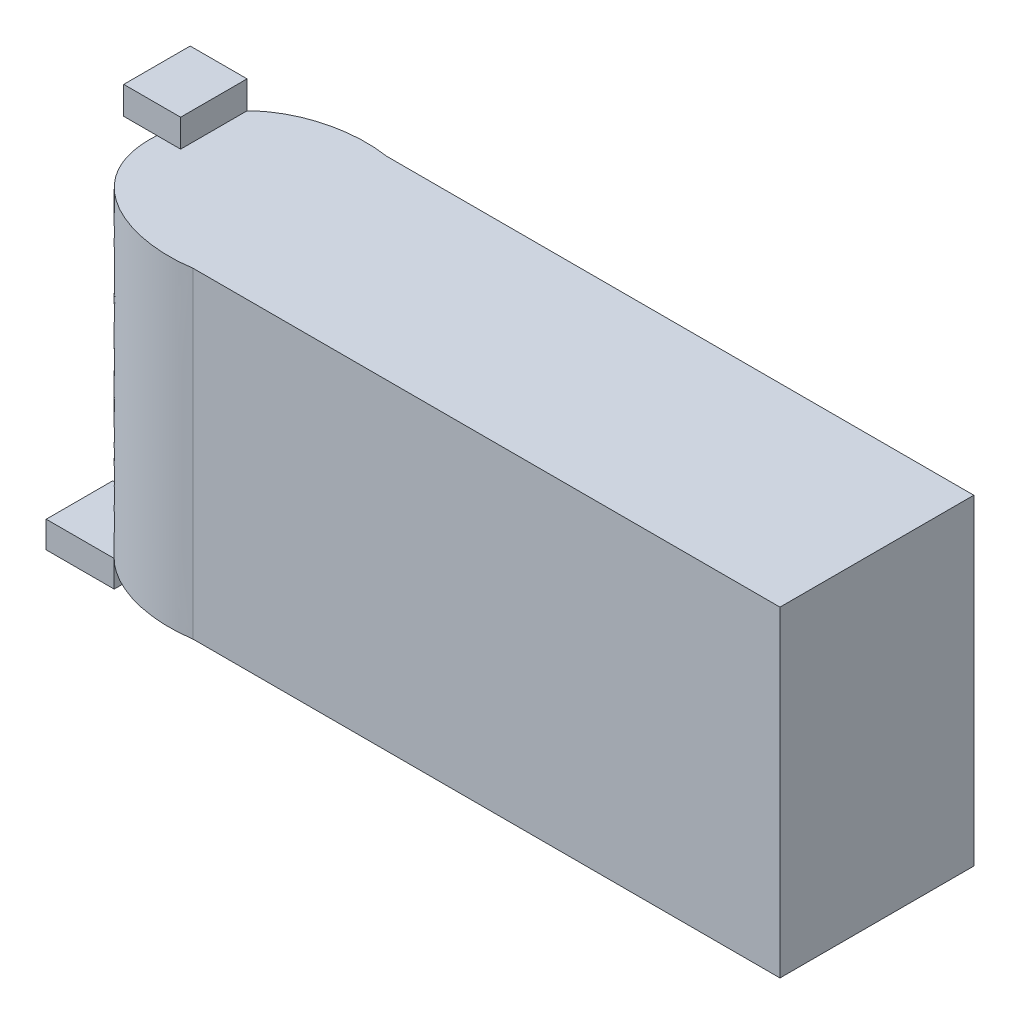
SolidWorks part; units mm, degrees
ref_plane "Front Plane" through (0, 0, 0) normal (0, 0, 1) x (1, 0, 0)
ref_plane "Top Plane" through (0, 0, 0) normal (0, 1, 0) x (1, 0, 0)
ref_plane "Right Plane" through (0, 0, 0) normal (1, 0, 0) x (0, 0, -1)
sketch "Sketch2" plane through (0, 0, 0) normal (0, 1, 0) x (1, 0, 0)
  line L0 (-26.5, 0) -> (-38.5, 0) construction
  line L1 (-26.5, -8.75) -> (26.5, -8.75)
  line L2 (-26.5, -8.75) -> (-26.5, 8.75)
  line L3 (-26.5, 8.75) -> (26.5, 8.75)
  line L4 (26.5, -8.75) -> (26.5, 8.75)
  line L5 (-26.5, -8.75) -> (26.5, 8.75) construction
  line L6 (-26.5, 8.75) -> (26.5, -8.75) construction
  line L7 (-26.5, 6.75) -> (-35.5, 6.75) construction
  line L8 (-26.5, 8.75) -> (-30.5, 8.75) construction
  spline S0 degree 3 poles (-26.5, 8.75) (-31.8446, 9.5987) (-38.9648, 6.9537) (-38.5, 0) knots 0 0 0 0 1 1 1 1
  spline S1 degree 3 poles (-26.5, -8.75) (-31.8446, -9.5987) (-38.9648, -6.9537) (-38.5, 0) knots 0 0 0 0 1 1 1 1
  point P0 (0, 0)
  dimension "D1" = 53
  dimension "D2" = 17.5
  dimension "D3" = 12
  dimension "D4" = 9
  dimension "D5" = 2
  dimension "D6" = 4
extrude "Boss-Extrude1" add sketch "Sketch2" along normal blind 29 contours L1 L4 L3 L2 | S1 L2 S0
sketch "Sketch3" plane through (0, 29, 0) normal (0, 1, 0) x (1, 0, 0)
  line L0 (-38.5, 6) -> (-36.3652, 6)
  line L1 (-38.5, 0) -> (-41.5, 0)
  line L2 (-38.5, 0) -> (-38.5, 6) construction
  line L3 (-38.5, 6) -> (-41.5, 6)
  line L4 (-41.5, 0) -> (-41.5, 6)
  line L5 (-36.3652, 6) -> (-36.3652, 0)
  line L6 (-36.3652, 0) -> (-38.5, 0)
  spline S0 degree 3 poles (-26.5, 8.75) (-31.8446, 9.5987) (-38.9648, 6.9537) (-38.5, 0) knots 0 0 0 0 1 1 1 1 construction
  dimension "D1" = 6
  dimension "D2" = 3
extrude "Boss-Extrude2" add sketch "Sketch3" along normal blind 2.5
sketch "Sketch4" plane through (0, 0, 0) normal (0, -1, 0) x (1, 0, 0)
  line L0 (-38.5, 6) -> (-36.3652, 6)
  line L1 (-38.5, 0) -> (-42.5, 0)
  line L2 (-38.5, 0) -> (-38.5, 6) construction
  line L3 (-38.5, 6) -> (-42.5, 6)
  line L4 (-42.5, 0) -> (-42.5, 6)
  line L5 (-36.3652, 6) -> (-36.3652, 0)
  line L6 (-36.3652, 0) -> (-38.5, 0)
  spline S0 degree 3 poles (-26.5, 8.75) (-31.8446, 9.5987) (-38.9648, 6.9537) (-38.5, 0) knots 0 0 0 0 1 1 1 1 construction
  point P0 (-38.5, 0)
  dimension "D1" = 6
  dimension "D2" = 4
extrude "Boss-Extrude3" add sketch "Sketch4" along normal blind 2.4
